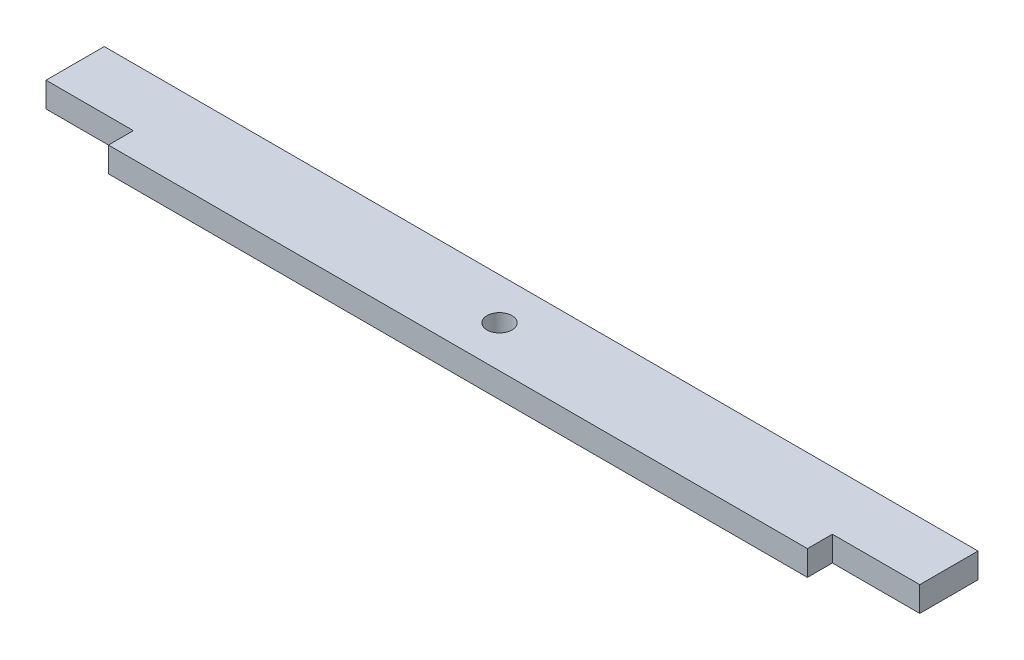
SolidWorks part; units mm, degrees
ref_plane "Front" through (0, 0, 0) normal (0, 0, 1) x (1, 0, 0)
ref_plane "Top" through (0, 0, 0) normal (0, 1, 0) x (1, 0, 0)
ref_plane "Right" through (0, 0, 0) normal (1, 0, 0) x (0, 0, -1)
sketch "Sketch1" plane through (0, 0, 0) normal (0, 1, 0) x (1, 0, 0)
  line L1 (-52.5, 5) -> (52.5, 5)
  line L2 (-52.5, 5) -> (-52.5, -5)
  line L3 (-52.5, -5) -> (52.5, -5)
  line L4 (52.5, 5) -> (52.5, -5)
  line L5 (-52.5, 5) -> (52.5, -5) construction
  line L6 (-52.5, -5) -> (52.5, 5) construction
  circle A0 centre (0, 0) radius 1.5
  point P0 (0, 0)
  dimension "D3" = 3
  dimension "D1" = 105
  dimension "D2" = 10
extrude "Boss-Extrude1" add sketch "Sketch1" along normal blind 3
sketch "Sketch2" plane through (0, 3, 0) normal (0, 1, 0) x (1, 0, 0)
  line L0 (-52.5, -5) -> (-42, -5)
  line L1 (-52.5, -5) -> (52.5, -5) construction
  line L2 (-42, -5) -> (-42, -2)
  line L3 (-42, -2) -> (-52.5, -2)
  line L6 (-52.5, -2) -> (-52.5, -5)
  dimension "D1" = 10.5
  dimension "D2" = 3
extrude "Cut-Extrude1" cut sketch "Sketch2" against normal through all
mirror "Mirror2" about plane through (0, 0, 0) normal (1, 0, 0) of "Cut-Extrude1"
